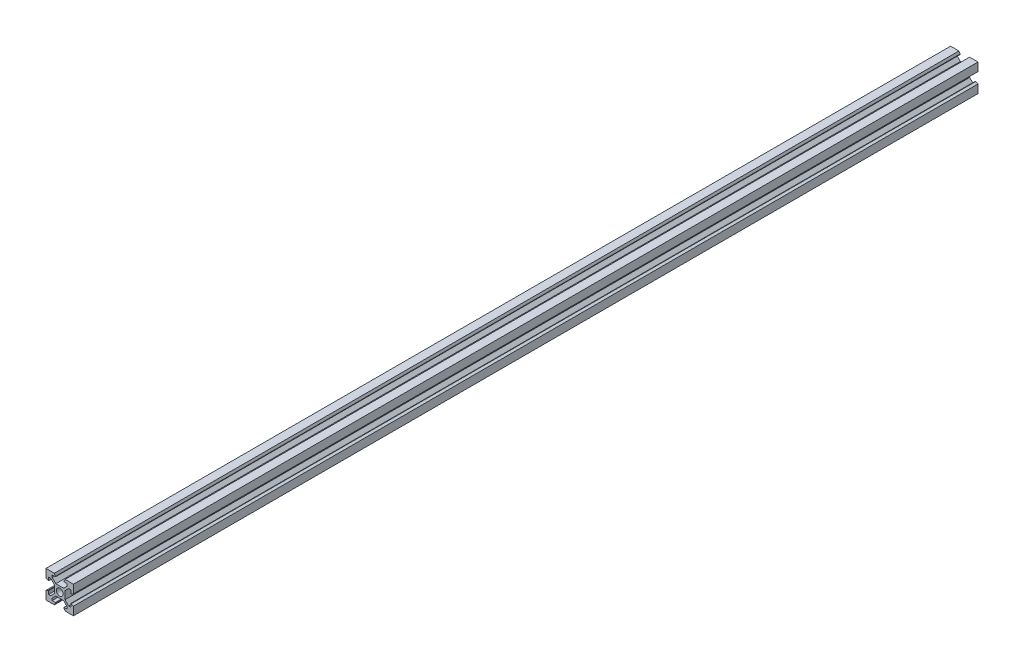
SolidWorks part; units mm, degrees
ref_plane "Front Plane" through (0, 0, 0) normal (0, 0, 1) x (1, 0, 0)
ref_plane "Top Plane" through (0, 0, 0) normal (0, 1, 0) x (1, 0, 0)
ref_plane "Right Plane" through (0, 0, 0) normal (1, 0, 0) x (0, 0, -1)
sketch "Sketch1" plane through (0, 0, 0) normal (0, 0, 1) x (1, 0, 0)
  line L0 (0, 20) -> (0, 13.8958)
  line L1 (0, 0) -> (20, 0)
  line L2 (0, 0) -> (0, 20)
  line L3 (0, 20) -> (20, 20)
  line L4 (20, 0) -> (20, 20)
  line L5 (0, 13.8958) -> (1.56, 13.1)
  line L6 (1.56, 13.1) -> (1.9, 13.1)
  line L7 (1.9, 13.1) -> (1.9, 15.5)
  line L8 (1.9, 15.5) -> (3.4393, 15.5)
  line L9 (3.4393, 15.5) -> (6.2656, 12.6737)
  line L10 (6.2656, 12.6737) -> (7.3263, 13.7344)
  line L11 (7.3263, 13.7344) -> (4.5, 16.5607)
  line L12 (4.5, 16.5607) -> (4.5, 18.1)
  line L13 (4.5, 18.1) -> (6.9, 18.1)
  line L14 (6.9, 18.1) -> (6.9, 18.44)
  line L15 (6.9, 18.44) -> (6.1, 20)
  line L16 (6.1, 20) -> (0, 20)
  line L17 (10, 10) -> (6.1, 13.9)
  line L18 (6.1, 6.1) -> (13.9, 6.1)
  line L19 (6.1, 6.1) -> (6.1, 13.9)
  line L20 (6.1, 13.9) -> (13.9, 13.9)
  line L21 (13.9, 6.1) -> (13.9, 13.9)
  line L22 (6.796, 13.204) -> (4.0494, 15.9506)
  line L23 (10, 10) -> (10, 24.9145) construction
  line L24 (13.1, 18.44) -> (13.9, 20)
  line L25 (13.1, 18.1) -> (13.1, 18.44)
  line L26 (15.5, 18.1) -> (13.1, 18.1)
  line L27 (15.5, 16.5607) -> (15.5, 18.1)
  line L28 (12.6737, 13.7344) -> (15.5, 16.5607)
  line L29 (13.7344, 12.6737) -> (12.6737, 13.7344)
  line L30 (16.5607, 15.5) -> (13.7344, 12.6737)
  line L31 (18.1, 15.5) -> (16.5607, 15.5)
  line L32 (18.1, 13.1) -> (18.1, 15.5)
  line L33 (18.44, 13.1) -> (18.1, 13.1)
  line L34 (20, 13.8958) -> (18.44, 13.1)
  line L35 (10, 10) -> (22.1718, 10)
  line L36 (20, 6.1042) -> (18.44, 6.9)
  line L37 (18.44, 6.9) -> (18.1, 6.9)
  line L38 (18.1, 6.9) -> (18.1, 4.5)
  line L39 (18.1, 4.5) -> (16.5607, 4.5)
  line L40 (16.5607, 4.5) -> (13.7344, 7.3263)
  line L41 (13.7344, 7.3263) -> (12.6737, 6.2656)
  line L42 (12.6737, 6.2656) -> (15.5, 3.4393)
  line L43 (15.5, 3.4393) -> (15.5, 1.9)
  line L44 (15.5, 1.9) -> (13.1, 1.9)
  line L45 (13.1, 1.9) -> (13.1, 1.56)
  line L46 (13.1, 1.56) -> (13.9, 0)
  line L47 (6.9, 1.56) -> (6.1, 0)
  line L48 (6.9, 1.9) -> (6.9, 1.56)
  line L49 (4.5, 1.9) -> (6.9, 1.9)
  line L50 (4.5, 3.4393) -> (4.5, 1.9)
  line L51 (7.3263, 6.2656) -> (4.5, 3.4393)
  line L52 (6.2656, 7.3263) -> (7.3263, 6.2656)
  line L53 (3.4393, 4.5) -> (6.2656, 7.3263)
  line L54 (1.9, 4.5) -> (3.4393, 4.5)
  line L55 (1.9, 6.9) -> (1.9, 4.5)
  line L56 (1.56, 6.9) -> (1.9, 6.9)
  line L57 (0, 6.1042) -> (1.56, 6.9)
  circle A0 centre (10, 10) radius 2.5
  point P21 (2.6697, 15.5)
  dimension "D3" = 5
  dimension "D1" = 20
  dimension "D2" = 20
  dimension "D4" = 10
  dimension "D5" = 10
  dimension "D6" = 7.8
  dimension "D7" = 7.8
  dimension "D8" = 6.1
  dimension "D9" = 6.1
  dimension "D10" = 6.9
  dimension "D11" = 6.9
  dimension "D12" = 6.1042
  dimension "D13" = 6.1
  dimension "D14" = 0.34
  dimension "D15" = 0.34
  dimension "D16" = 1.9
  dimension "D17" = 4.5
  dimension "D18" = 4.5
  dimension "D19" = 1.5
  dimension "D20" = 1.9
extrude "Boss-Extrude1" add sketch "Sketch1" along normal blind 660
